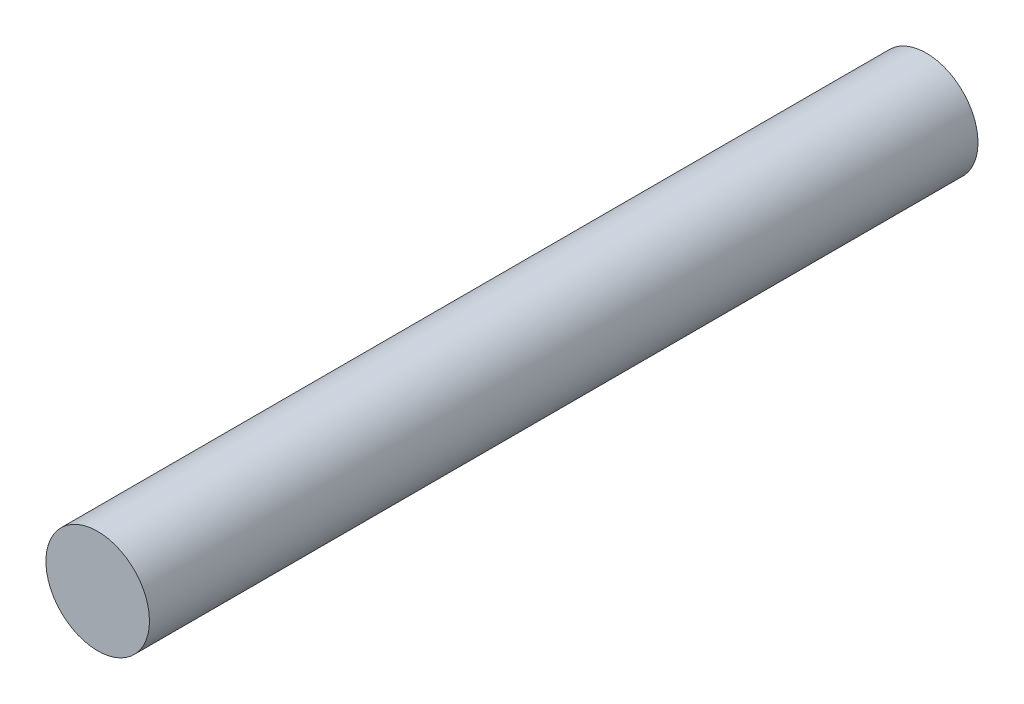
SolidWorks part; units mm, degrees
material "ABS"
ref_plane "Front Plane" through (0, 0, 0) normal (0, 0, 1) x (1, 0, 0)
ref_plane "Top Plane" through (0, 0, 0) normal (0, 1, 0) x (1, 0, 0)
ref_plane "Right Plane" through (0, 0, 0) normal (1, 0, 0) x (0, 0, -1)
sketch "Sketch1" plane through (0, 0, 0) normal (0, 0, 1) x (1, 0, 0)
  circle A0 centre (0, 0) radius 1.5875
extrude "Boss-Extrude1" add sketch "Sketch1" along normal blind 25.4
